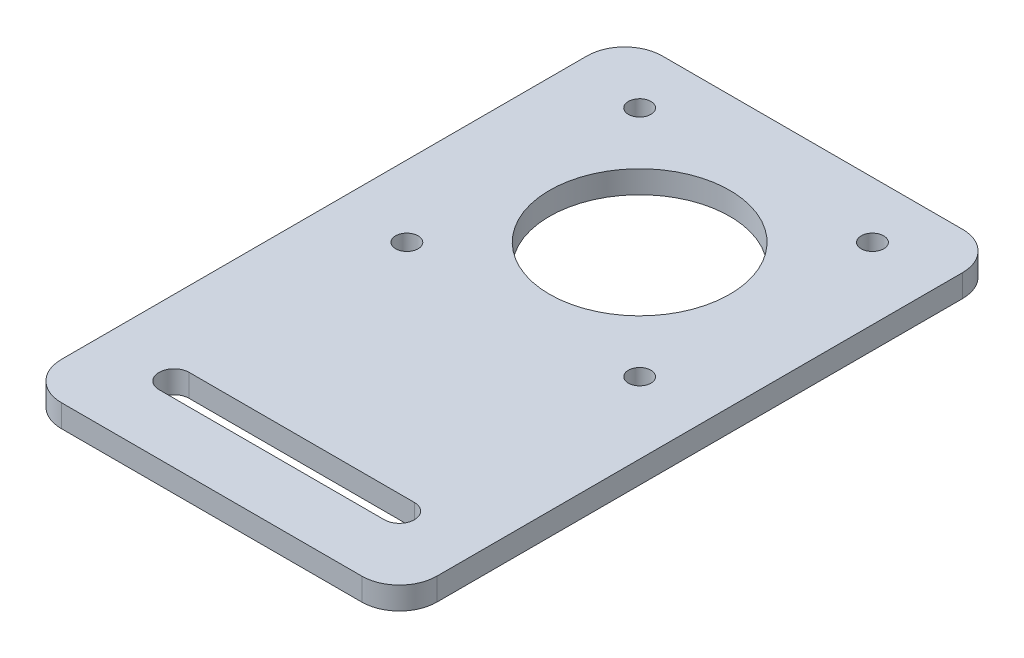
SolidWorks part; units mm, degrees
ref_plane "Front Plane" through (0, 0, 0) normal (0, 0, 1) x (1, 0, 0)
ref_plane "Top Plane" through (0, 0, 0) normal (0, 1, 0) x (1, 0, 0)
ref_plane "Right Plane" through (0, 0, 0) normal (1, 0, 0) x (0, 0, -1)
sketch "Sketch1" plane through (0, 0, 0) normal (0, 1, 0) x (1, 0, 0)
  line L1 (25, 40) -> (-25, 40)
  line L2 (25, 40) -> (25, -40)
  line L3 (25, -40) -> (-25, -40)
  line L4 (-25, 40) -> (-25, -40)
  line L5 (25, 40) -> (-25, -40) construction
  line L6 (25, -40) -> (-25, 40) construction
  point P0 (0, 0)
  dimension "D1" = 50
  dimension "D2" = 80
extrude "Boss-Extrude1" add sketch "Sketch1" along normal blind 3
sketch "Sketch2" plane through (0, 3, 0) normal (0, 1, 0) x (1, 0, 0)
  line L0 (25, 40) -> (-25, 40) construction
  line L1 (-1001.5607, -30) -> (48998.4393, -30) construction
  line L2 (-1001.5607, -40) -> (48998.4393, -40) construction
  line L3 (-15.5, 32.5) -> (15.5, 32.5) construction
  line L4 (-15.5, 32.5) -> (-15.5, 1.5) construction
  line L5 (-15.5, 1.5) -> (15.5, 1.5) construction
  line L6 (15.5, 32.5) -> (15.5, 1.5) construction
  line L7 (-15.5, 32.5) -> (15.5, 1.5) construction
  line L8 (-15.5, 1.5) -> (15.5, 32.5) construction
  line L9 (-1001.5607, -20) -> (48998.4393, -20) construction
  line L10 (-25, -40) -> (25, -40) construction
  line L11 (0, -1000) -> (0, 49000) construction
  line L12 (-15, -30) -> (15, -30) construction
  line L13 (-15, -28) -> (15, -28)
  line L14 (-15, -32) -> (15, -32)
  arc A0 (-15, -28) -> (-15, -32) centre (-15, -30) ccw
  arc A1 (15, -32) -> (15, -28) centre (15, -30) ccw
  circle A2 centre (15.5, 32.5) radius 1.5
  circle A3 centre (-15.5, 32.5) radius 1.5
  circle A4 centre (-15.5, 1.5) radius 1.5
  circle A5 centre (15.5, 1.5) radius 1.5
  circle A6 centre (0, 17) radius 12
  point P2 (0, 40)
  point P4 (0, 17)
  point P22 (0, -30)
  dimension "D4" = 2
  dimension "D6" = 3
  dimension "D8" = 24
  dimension "D1" = 31
  dimension "D5" = 30
  dimension "D7" = 23
  dimension "D2" = 10
  dimension "D3" = 10
extrude "Cut-Extrude1" cut sketch "Sketch2" against normal through all
fillet "Fillet1" radius 5 4 edges at (25, 1.5, 40) (-25, 1.5, 40) (-25, 1.5, -40) (25, 1.5, -40)
